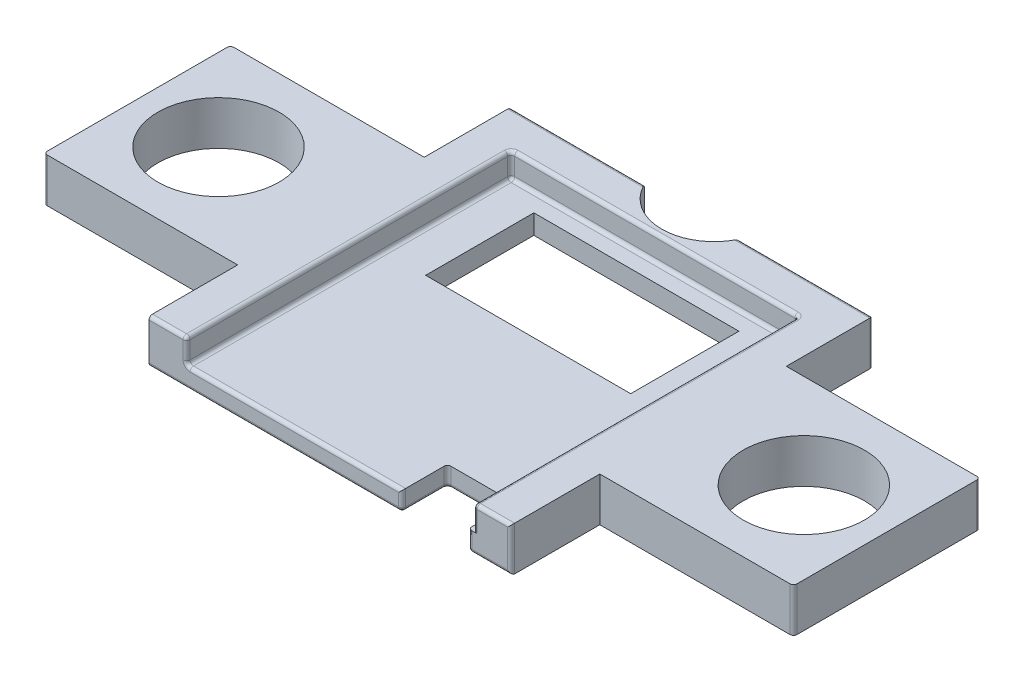
SolidWorks part; units mm, degrees
ref_plane "Front Plane" through (0, 0, 0) normal (0, 0, 1) x (1, 0, 0)
ref_plane "Top Plane" through (0, 0, 0) normal (0, 1, 0) x (1, 0, 0)
ref_plane "Right Plane" through (0, 0, 0) normal (1, 0, 0) x (0, 0, -1)
sketch "Sketch1" plane through (0, 0, 0) normal (0, 1, 0) x (1, 0, 0)
  line L1 (-10.375, -10.375) -> (10.375, -10.375)
  line L2 (-10.375, -10.375) -> (-10.375, 10.375)
  line L3 (-10.375, 10.375) -> (10.375, 10.375)
  line L4 (10.375, -10.375) -> (10.375, 10.375)
  line L5 (-10.375, -10.375) -> (10.375, 10.375) construction
  line L6 (-10.375, 10.375) -> (10.375, -10.375) construction
  line L7 (-5.875, 7.175) -> (5.875, 7.175)
  line L8 (-5.875, 7.175) -> (-5.875, 0.975)
  line L9 (-5.875, 0.975) -> (5.875, 0.975)
  line L10 (5.875, 7.175) -> (5.875, 0.975)
  point P0 (0, 0)
  dimension "D1" = 20.75
  dimension "D2" = 6.2
  dimension "D3" = 11.75
  dimension "D4" = 3.2
  dimension "D5" = 4.5
  dimension "D6" = 4.5
extrude "Boss-Extrude1" add sketch "Sketch1" along normal blind 1.12
sketch "Sketch2" plane through (0, 1.12, 0) normal (0, 1, 0) x (1, 0, 0)
  line L0 (10.375, -10.375) -> (10.375, 10.375) construction
  line L1 (-10.375, 10.375) -> (10.375, 10.375)
  line L2 (-10.375, 10.375) -> (-10.375, 8.225)
  line L3 (-10.375, 8.225) -> (10.375, 8.225)
  line L4 (10.375, 10.375) -> (10.375, 8.225)
  line L5 (-10.375, -10.375) -> (10.375, -10.375) construction
  line L6 (10.375, 8.225) -> (8.225, 8.225)
  line L7 (10.375, 8.225) -> (10.375, -10.375)
  line L8 (10.375, -10.375) -> (8.225, -10.375)
  line L9 (8.225, 8.225) -> (8.225, -10.375)
  line L11 (-10.375, 8.225) -> (-8.225, 8.225)
  line L12 (-10.375, 8.225) -> (-10.375, -10.375)
  line L13 (-10.375, -10.375) -> (-8.225, -10.375)
  line L14 (-8.225, 8.225) -> (-8.225, -10.375)
  line M13 (10.375, -10.375) -> (10.375, 10.375)
  line M14 (10.375, 10.375) -> (-10.375, 10.375)
  line M15 (-10.375, 10.375) -> (-10.375, -10.375)
  line M16 (-10.375, -10.375) -> (10.375, -10.375)
  dimension "D1" = 2.15
  dimension "D2" = 2.15
  dimension "D3" = 2.15
extrude "Boss-Extrude2" add sketch "Sketch2" along normal blind 1.4 contours L3 M15 M13 M14 | L14 L3 M15 M16 | L7 L8 L9 L6
sketch "Sketch3" plane through (0, 1.12, 0) normal (0, 1, 0) x (1, 0, 0)
  line L0 (-8.225, -10.375) -> (8.225, -10.375) construction
  line L1 (7.925, -10.375) -> (4.1284, -10.375)
  line L2 (7.925, -10.375) -> (7.925, -7.975)
  line L3 (7.725, -7.775) -> (4.3284, -7.775)
  line L4 (4.1284, -10.375) -> (4.1284, -7.975)
  line L5 (8.225, 8.225) -> (8.225, -10.375) construction
  arc A0 (4.3284, -7.775) -> (4.1284, -7.975) centre (4.3284, -7.975) ccw
  arc A1 (7.925, -7.975) -> (7.725, -7.775) centre (7.725, -7.975) ccw
  dimension "D3" = 0.2
  dimension "D1" = 0.3
  dimension "D2" = 2.6
extrude "Cut-Extrude1" cut sketch "Sketch3" against normal through all
fillet "Fillet1" radius 0.2 25 edges at (-8.225, 1.82, -8.225) (0, 1.12, -8.225) (-8.225, 2.52, 1.075) (-8.225, 1.82, 10.375) (-9.3, 2.52, 10.375) (0, 2.52, -8.225) (8.225, 2.52, 1.075) (0, 2.52, -10.375) (-8.225, 1.12, 1.075) (8.225, 1.82, -8.225) (9.3, 2.52, 10.375) (8.225, 1.82, 10.375) (-3.1233, 0, 10.375) (0, 0, -10.375) (9.15, 0, 10.375) (7.925, 0, 9.175) (7.925, 0.56, 10.375) (4.1284, 0, 9.175) (4.1284, 0.56, 10.375) (4.187, 0, 7.8336) (6.0267, 0, 7.775) (7.8664, 0, 7.8336) (10.375, 1.26, 10.375) (-10.375, 1.26, -10.375) (10.375, 1.26, -10.375)
sketch "Sketch5" plane through (0, 2.52, 0) normal (0, 1, 0) x (1, 0, 0)
  line L0 (-10.375, 10.175) -> (-10.375, -10.175) construction
  line L1 (-10.375, 5.3925) -> (-21.2755, 5.3925)
  line L2 (-10.375, 5.3925) -> (-10.375, -5.2965)
  line L3 (-10.375, -5.2965) -> (-21.2755, -5.2965)
  line L4 (-21.4755, 5.1925) -> (-21.4755, -5.0965)
  line L5 (10.375, -10.175) -> (10.375, 10.175) construction
  line L6 (10.375, 5.3925) -> (21.2755, 5.3925)
  line L7 (10.375, 5.3925) -> (10.375, -5.2965)
  line L8 (10.375, -5.2965) -> (21.2755, -5.2965)
  line L9 (21.4755, 5.1925) -> (21.4755, -5.0965)
  line L10 (-16.77, 0) -> (16.77, 0) construction
  line L11 (-10.375, 5.3925) -> (10.375, 5.3925) construction
  line L12 (-10.375, -5.2965) -> (10.375, -5.2965) construction
  circle A0 centre (-16.77, 0) radius 3.475
  circle A1 centre (16.77, 0) radius 3.475
  arc A2 (-21.4755, -5.0965) -> (-21.2755, -5.2965) centre (-21.2755, -5.0965) ccw
  arc A3 (21.2755, -5.2965) -> (21.4755, -5.0965) centre (21.2755, -5.0965) ccw
  arc A4 (21.4755, 5.1925) -> (21.2755, 5.3925) centre (21.2755, 5.1925) ccw
  arc A5 (-21.2755, 5.3925) -> (-21.4755, 5.1925) centre (-21.2755, 5.1925) ccw
  point P24 (0, 0)
  point P28 (0, 0)
  dimension "D1" = 0.2
  dimension "D5" = 6.95
  dimension "D2" = 33.54
extrude "Boss-Extrude3" add sketch "Sketch5" against normal up to surface (2.52 mm away) up to face at (3.616, 0, 5.1284)
sketch "Sketch6" plane through (0, 2.52, 0) normal (0, 1, 0) x (1, 0, 0)
  circle A0 centre (0, 11.63) radius 3
  dimension "D1" = 6
extrude "Cut-Extrude2" cut sketch "Sketch6" against normal blind 10
equation "\"D3@Sketch2\"=\"D1@Sketch2\""
equation "\"D2@Sketch2\"=\"D1@Sketch2\""
